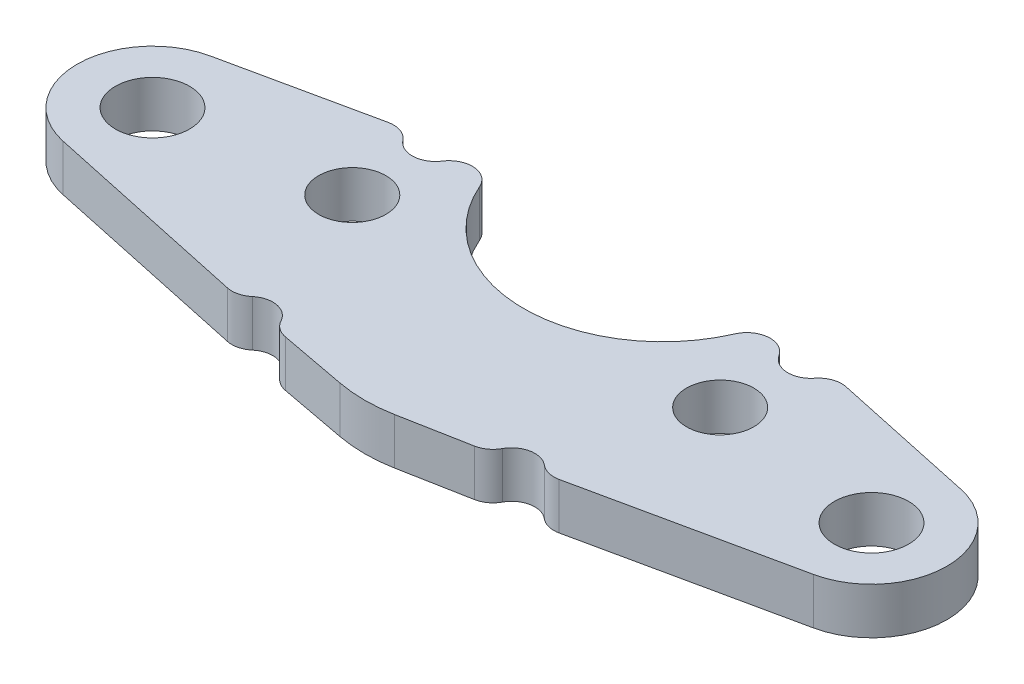
SolidWorks part; units mm, degrees
ref_plane "Front Plane" through (0, 0, 0) normal (0, 0, 1) x (1, 0, 0)
ref_plane "Top Plane" through (0, 0, 0) normal (0, 1, 0) x (1, 0, 0)
ref_plane "Right Plane" through (0, 0, 0) normal (1, 0, 0) x (0, 0, -1)
ref_plane "Plane1" through (0, 0, 0) normal (0, -1, 0) x (1, 0, 0)
sketch "Sketch1" plane through (0, 0, 0) normal (0, -1, 0) x (1, 0, 0)
  line L0 (-1000, 0) -> (49000, 0) construction
  line L1 (16.1814, -3.1778) -> (9.8729, -4.5305)
  line L2 (7.1507, 5.1143) -> (16.1814, 3.1778)
  line L3 (-1.1749, 6.2398) -> (-4.0769, 5.6934)
  line L4 (-7.1507, 5.1143) -> (-16.1814, 3.1778)
  line L5 (-16.1814, -3.1778) -> (-9.8729, -4.5305)
  line L6 (0, -1000) -> (0, 49000) construction
  line L7 (1.1749, 6.2398) -> (4.0769, 5.6934)
  circle A0 centre (-15.5, 0) radius 1.6
  circle A1 centre (15.5, 0) radius 1.6
  circle A2 centre (7.9316, -1.0442) radius 1.45
  circle A3 centre (-7.9316, -1.0442) radius 1.45
  arc A4 (-9.8729, -4.5305) -> (-8.8803, -4.1749) centre (-9.6632, -3.5528) ccw
  arc A5 (-8.8803, -4.1749) -> (-7.2584, -4.2528) centre (-8.0973, -4.797) cw
  arc A6 (-7.2584, -4.2528) -> (-5.5023, -4.1074) centre (-6.4194, -3.7087) ccw
  arc A7 (-5.5023, -4.1074) -> (5.5023, -4.1074) centre (0, -6.5) cw
  arc A8 (7.2584, -4.2528) -> (5.5023, -4.1074) centre (6.4194, -3.7087) cw
  arc A9 (8.8803, -4.1749) -> (7.2584, -4.2528) centre (8.0973, -4.797) ccw
  arc A10 (9.8729, -4.5305) -> (8.8803, -4.1749) centre (9.6632, -3.5528) cw
  arc A11 (16.1814, 3.1778) -> (16.1814, -3.1778) centre (15.5, 0) cw
  arc A12 (6.2955, 4.9002) -> (7.1507, 5.1143) centre (6.941, 4.1365) cw
  arc A13 (4.7709, 5.1873) -> (6.2955, 4.9002) centre (5.65, 5.664) ccw
  arc A14 (4.0769, 5.6934) -> (4.7709, 5.1873) centre (3.8919, 4.7106) cw
  arc A15 (1.1749, 6.2398) -> (-1.1749, 6.2398) centre (0, 0) ccw
  arc A16 (-4.0769, 5.6934) -> (-4.7709, 5.1873) centre (-3.8919, 4.7106) ccw
  arc A17 (-4.7709, 5.1873) -> (-6.2955, 4.9002) centre (-5.65, 5.664) cw
  arc A18 (-6.2955, 4.9002) -> (-7.1507, 5.1143) centre (-6.941, 4.1365) ccw
  arc A19 (-16.1814, 3.1778) -> (-16.1814, -3.1778) centre (-15.5, 0) ccw
  dimension "D1" = 1
  dimension "D2" = 6.5
  dimension "D3" = 2.9
  dimension "D4" = 3.2
  dimension "D5" = 15.5
  dimension "D6" = 7.9316
  dimension "D7" = 5.65
  dimension "D8" = 5.664
  dimension "D9" = 8.0973
  dimension "D10" = 4.7106
  dimension "D11" = 3.7087
  dimension "D12" = 6
  dimension "D13" = 6.3494
  dimension "D14" = 1.65
  dimension "D15" = 1.0442
  dimension "D16" = 4.1365
  dimension "D20" = 4.797
extrude "Boss-Extrude1" add sketch "Sketch1" against normal blind 2
